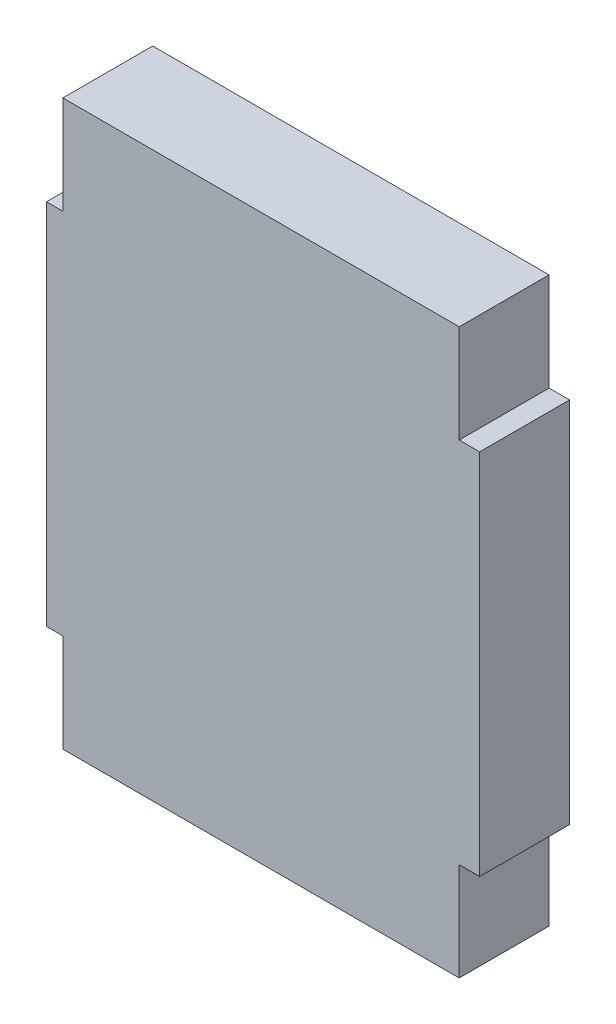
SolidWorks part; units mm, degrees
ref_plane "前视基准面" through (0, 0, 0) normal (0, 0, 1) x (1, 0, 0)
ref_plane "上视基准面" through (0, 0, 0) normal (0, 1, 0) x (1, 0, 0)
ref_plane "右视基准面" through (0, 0, 0) normal (1, 0, 0) x (0, 0, -1)
sketch "草图1" plane through (0, 0, 0) normal (0, 0, 1) x (1, 0, 0)
  line L0 (2.675, -2.25) -> (2.425, -2.25)
  line L1 (2.425, -2.25) -> (2.425, -3.45)
  line L2 (2.425, -3.45) -> (-2.425, -3.45)
  line L3 (-2.425, -3.45) -> (-2.425, -2.25)
  line L4 (-2.425, -2.25) -> (-2.625, -2.25)
  line L5 (-2.625, -2.25) -> (-2.625, 2.25)
  line L6 (-2.625, 2.25) -> (-2.425, 2.25)
  line L7 (-2.425, 2.25) -> (-2.425, 3.45)
  line L8 (-2.425, 3.45) -> (2.425, 3.45)
  line L9 (2.425, 3.45) -> (2.425, 2.25)
  line L10 (2.425, 2.25) -> (2.675, 2.25)
  line L11 (2.675, 2.25) -> (2.675, -2.25)
extrude "Component_Outline" add sketch "草图1" along normal blind 1.1 separate body
sketch3d "3D草图1"
  line L0 (0, 0, 0) -> (1, 0, 0)
  line L1 (0, 0, 0) -> (0, 1, 0)
  line L2 (0, 0, 0) -> (0, 0, 1)
  point P0 (0, 0, 0)
